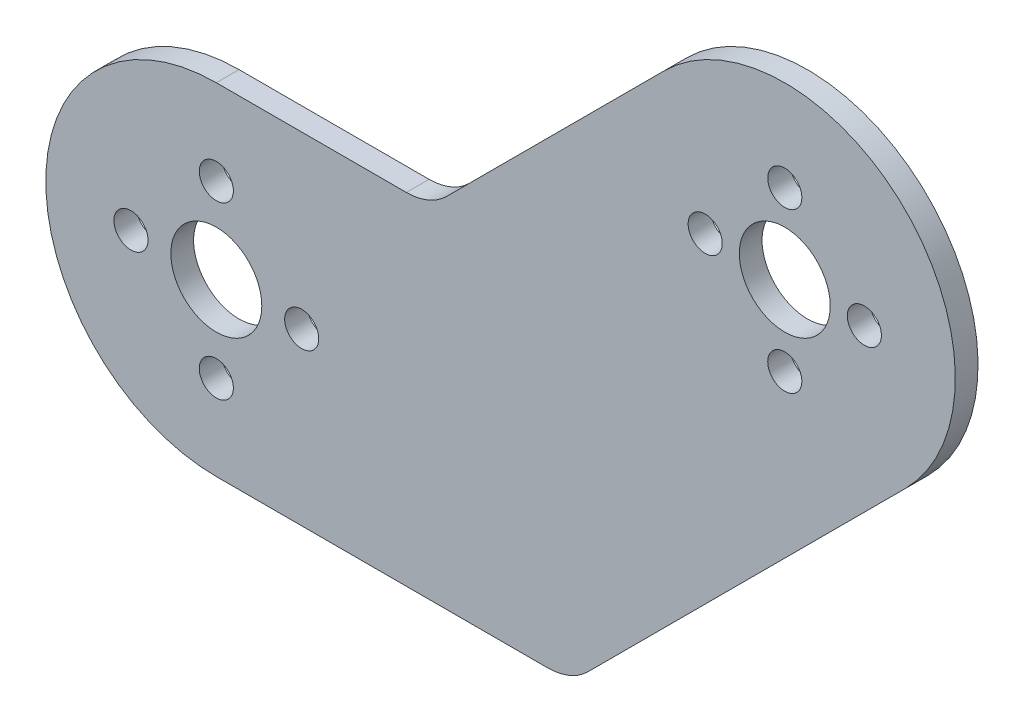
SolidWorks part; units mm, degrees
ref_plane "Alzado" through (0, 0, 0) normal (0, 0, 1) x (1, 0, 0)
ref_plane "Planta" through (0, 0, 0) normal (0, 1, 0) x (1, 0, 0)
ref_plane "Vista lateral" through (0, 0, 0) normal (1, 0, 0) x (0, 0, -1)
sketch "Croquis1" plane through (0, 0, 0) normal (0, 0, 1) x (1, 0, 0)
  circle A0 centre (0, 0) radius 4
  dimension "D1" = 8
sketch "Croquis2" plane through (0, 0, 0) normal (0, 0, 1) x (1, 0, 0)
  circle A0 centre (0, 7.5098) radius 1.5
sketch "Croquis3" plane through (0, 0, 0) normal (0, 0, 1) x (1, 0, 0)
  line L0 (0, 0) -> (50, 25) construction
  line L3 (0, 15) -> (16.7157, 15)
  line L4 (20.2513, 16.4645) -> (39.3934, 35.6066)
  line L6 (60.6066, 14.3934) -> (32.6777, -13.5355)
  line L8 (39.3934, 35.6066) -> (18.7868, 15) construction
  line L9 (29.1421, -15) -> (0, -15)
  line L10 (60.6066, 14.3934) -> (31.2132, -15) construction
  arc A0 (0, 15) -> (0, -15) centre (0, 0) ccw
  arc A1 (39.3934, 35.6066) -> (60.6066, 14.3934) centre (50, 25) cw
  arc A2 (16.7157, 15) -> (20.2513, 16.4645) centre (16.7157, 20) ccw
  arc A3 (32.6777, -13.5355) -> (29.1421, -15) centre (29.1421, -10) cw
  dimension "D1" = 5
  dimension "D2" = 5
extrude "Saliente-Extruir1" add sketch "Croquis3" along normal blind 2
extrude "Cortar-Extruir1" cut sketch "Croquis1" along normal blind 2 contours A0
extrude "Cortar-Extruir2" cut sketch "Croquis2" along normal blind 2 contours A0
pattern_circular "MatrizC1" count 4 every 90 about axis through (0, 0, 0) along (0, 0, 1) of "Cortar-Extruir2"
sketch "Croquis4" plane through (0, 0, 2) normal (0, 0, 1) x (1, 0, 0)
  circle A0 centre (50, 25) radius 4
extrude "Cortar-Extruir3" cut sketch "Croquis4" against normal blind 2
sketch "Croquis5" plane through (0, 0, 2) normal (0, 0, 1) x (1, 0, 0)
  circle A0 centre (50, 32) radius 1.5
extrude "Cortar-Extruir4" cut sketch "Croquis5" against normal blind 2
pattern_circular "MatrizC2" count 4 every 90 about axis through (50, 25, 0) along (0, 0, 1) of "Cortar-Extruir4"
